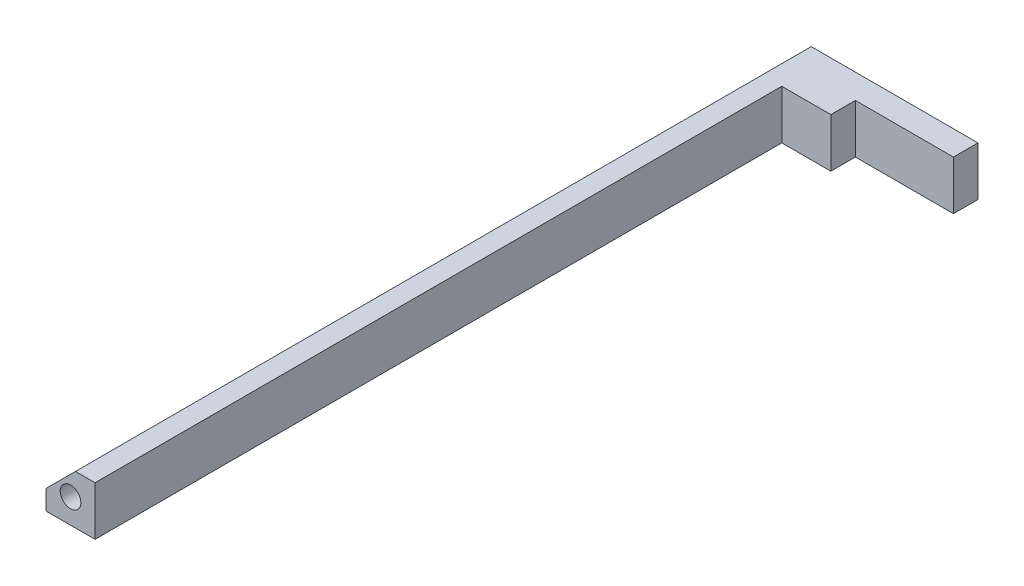
SolidWorks part; units mm, degrees
material "ABS"
ref_plane "Płaszczyzna przednia" through (0, 0, 0) normal (0, 0, 1) x (1, 0, 0)
ref_plane "Płaszczyzna górna" through (0, 0, 0) normal (0, 1, 0) x (1, 0, 0)
ref_plane "Płaszczyzna prawa" through (0, 0, 0) normal (1, 0, 0) x (0, 0, -1)
sketch "Szkic1" plane through (0, 0, 0) normal (0, 1, 0) x (1, 0, 0)
  line L0 (0, 0) -> (0, 150)
  line L1 (0, 150) -> (40, 150)
  line L2 (40, 150) -> (40, 145)
  line L3 (40, 145) -> (20, 145)
  line L4 (20, 145) -> (20, 140)
  line L5 (20, 140) -> (10, 140)
  line L6 (10, 140) -> (10, 0)
  line L7 (10, 0) -> (0, 0)
  dimension "D1" = 140
  dimension "D2" = 5
  dimension "D3" = 5
  dimension "D4" = 20
  dimension "D5" = 10
  dimension "D6" = 10
extrude "Dodanie-wyciągnięcie1" add sketch "Szkic1" along normal blind 10
sketch "Szkic2" plane through (0, 0, 0) normal (0, -1, 0) x (1, 0, 0)
  line L0 (0, 0) -> (0, -27) construction
  line L1 (0, -150) -> (0, 0) construction
  line L2 (0, -27) -> (7.2, -27) construction
  line L3 (7.2, -27) -> (7.2, -123) construction
  circle A0 centre (7.2, -27) radius 2.1
  circle A1 centre (7.2, -123) radius 2.1
  dimension "D2" = 4.2
  dimension "D4" = 4.2
  dimension "D1" = 27
  dimension "D3" = 96
  dimension "D5" = 7.2
extrude "Wytnij-wyciągnięcie1" cut sketch "Szkic2" against normal blind 4
sketch "Szkic3" plane through (0, 0, 0) normal (0, 0, 1) x (1, 0, 0)
  line L0 (0, 0) -> (5, 0) construction
  line L1 (0, 0) -> (10, 0) construction
  line L2 (5, 0) -> (5, 5) construction
  circle A0 centre (5, 5) radius 2.1
  dimension "D3" = 4.2
  dimension "D1" = 5
  dimension "D2" = 5
extrude "Wytnij-wyciągnięcie2" cut sketch "Szkic3" against normal blind 4
chamfer "Sfazowanie1" distance 6 angle 45 1 edges at (0, 10, -75)
